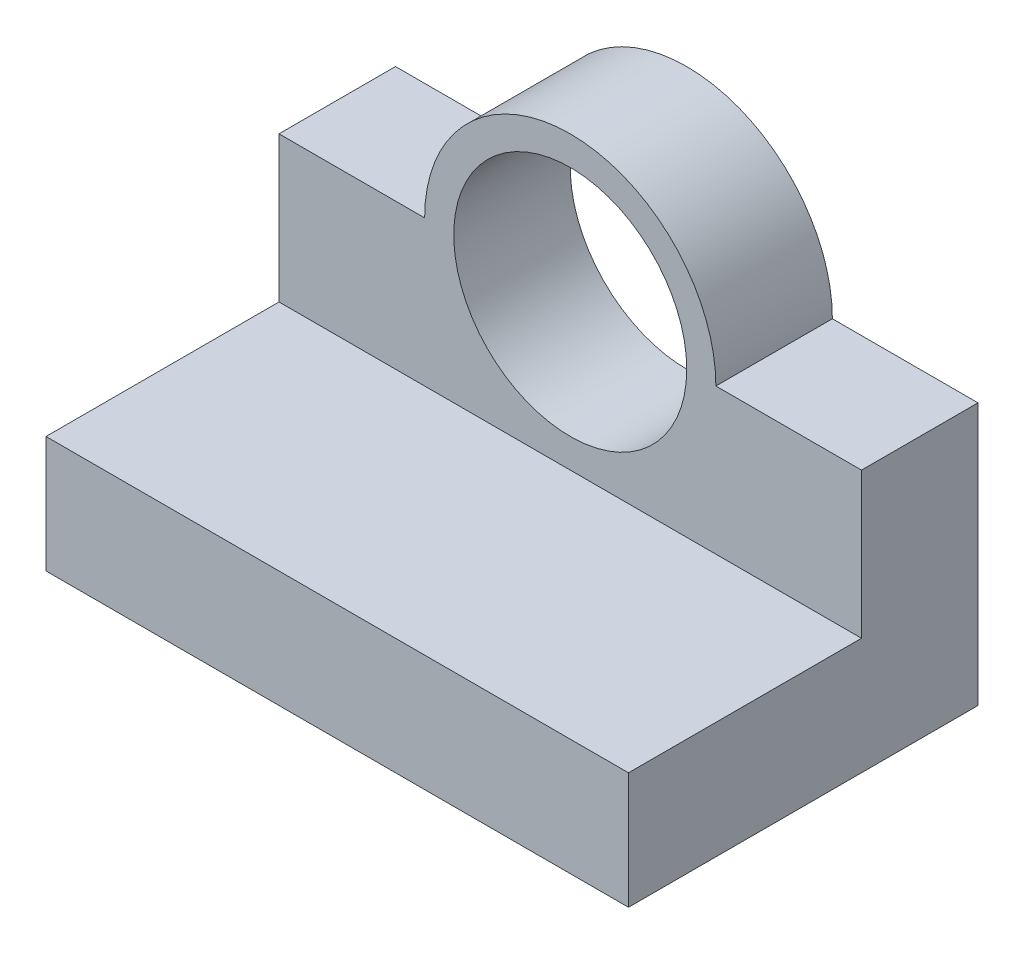
SolidWorks part; units mm, degrees
ref_plane "Front Plane" through (0, 0, 0) normal (0, 0, 1) x (1, 0, 0)
ref_plane "Top Plane" through (0, 0, 0) normal (0, 1, 0) x (1, 0, 0)
ref_plane "Right Plane" through (0, 0, 0) normal (1, 0, 0) x (0, 0, -1)
sketch "Sketch1" plane through (0, 0, 0) normal (0, 0, 1) x (1, 0, 0)
  line L0 (0, 0) -> (100, 0)
  line L1 (100, 0) -> (100, 25)
  line L3 (0, 25) -> (0, 0)
  line L4 (75, 25) -> (100, 25)
  line L6 (0, 25) -> (25, 25)
  arc A0 (75, 25) -> (25, 25) centre (50, 25) ccw
  circle A1 centre (50, 25) radius 20
  dimension "D5" = 50
  dimension "D6" = 40
  dimension "D1" = 100
extrude "Boss-Extrude1" add sketch "Sketch1" along normal blind 20
sketch "Sketch2" plane through (0, 0, 0) normal (0, -1, 0) x (1, 0, 0)
  line L1 (0, 0) -> (100, 0)
  line L2 (0, 0) -> (0, 20)
  line L3 (0, 20) -> (100, 20)
  line L4 (100, 0) -> (100, 20)
extrude "Boss-Extrude2" add sketch "Sketch2" along normal blind 20
sketch "Sketch3" plane through (0, 0, 20) normal (0, 0, 1) x (1, 0, 0)
  line L0 (100, -20) -> (100, 25) construction
  line L1 (0, -20) -> (100, -20)
  line L2 (0, -20) -> (0, 0)
  line L3 (0, 0) -> (100, 0)
  line L4 (100, -20) -> (100, 0)
extrude "Boss-Extrude3" add sketch "Sketch3" along normal blind 40
